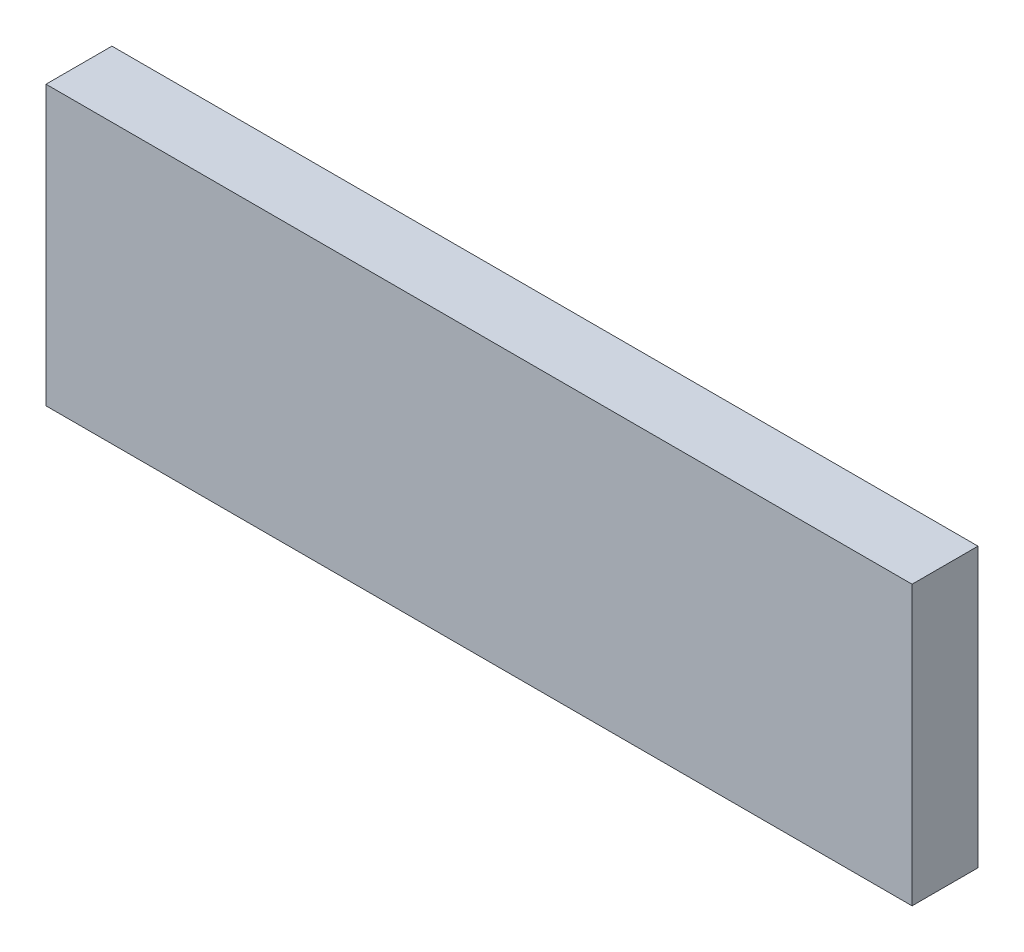
SolidWorks part; units mm, degrees
ref_plane "Front Plane" through (0, 0, 0) normal (0, 0, 1) x (1, 0, 0)
ref_plane "Top Plane" through (0, 0, 0) normal (0, 1, 0) x (1, 0, 0)
ref_plane "Right Plane" through (0, 0, 0) normal (1, 0, 0) x (0, 0, -1)
sketch "Sketch1" plane through (0, 0, 0) normal (0, 0, 1) x (1, 0, 0)
  line L1 (-13.135, 4.225) -> (13.135, 4.225)
  line L2 (-13.135, 4.225) -> (-13.135, -4.225)
  line L3 (-13.135, -4.225) -> (13.135, -4.225)
  line L4 (13.135, 4.225) -> (13.135, -4.225)
  line L5 (-13.135, 4.225) -> (13.135, -4.225) construction
  line L6 (-13.135, -4.225) -> (13.135, 4.225) construction
  point P0 (0, 0)
  dimension "D1" = 26.27
  dimension "D2" = 8.45
extrude "Boss-Extrude1" add sketch "Sketch1" along normal blind 2
